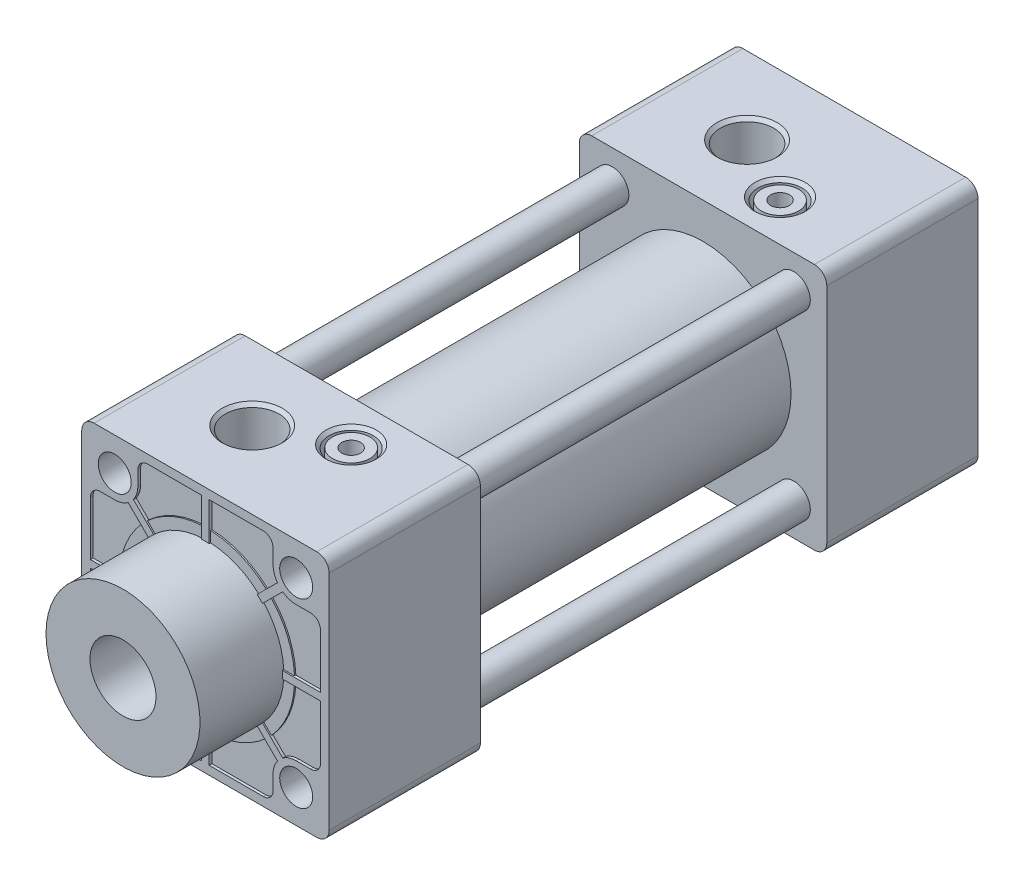
SolidWorks part; units mm, degrees
ref_plane "前视基准面" through (0, 0, 0) normal (0, 0, 1) x (1, 0, 0)
ref_plane "上视基准面" through (0, 0, 0) normal (0, 1, 0) x (1, 0, 0)
ref_plane "右视基准面" through (0, 0, 0) normal (1, 0, 0) x (0, 0, -1)
sketch "草图1" plane through (0, 0, 0) normal (1, 0, 0) x (0, 0, -1)
  line L0 (-59, 0) -> (59, 0) construction
  line L1 (0, 0) -> (0, 22.5) construction
  line L3 (-59, 0) -> (-59, 14) construction
  line L4 (-59, 14) -> (-74, 14) construction
  line L7 (-74, 14) -> (-74, 0) construction
  line L8 (25, 22.5) -> (118, 22.5) construction
  line L9 (-106, 0) -> (-106, 5) construction
  line L10 (-84, 0) -> (-106, 0) construction
  circle A0 centre (45, 5.5) radius 4.8645
  circle A1 centre (39, -6.5) radius 4
  point P2 (-106, 0)
  point P6 (-31.5, 0)
  point P10 (45, 5.5)
  point P11 (39, -6.5)
  point P15 (-49.5, 0)
  point P20 (31.5, 0)
  point P21 (-74, 6)
  point P22 (25, 22.5)
  point P25 (-97.2, 0)
  point P28 (-91.2, 0)
  point P29 (0, 16)
  dimension "O" = 9.729
  dimension "D3" = 8
  dimension "C" = 118
  dimension "S" = 45
  dimension "G" = 27.5
  dimension "N" = 14
  dimension "P" = 5.5
  dimension "Q" = 6
  dimension "R" = 6.5
  dimension "D" = 28
  dimension "F" = 15
  dimension "D4" = 8.8
  dimension "V" = 12
  dimension "行程" = 25
  dimension "C用" = 93
  dimension "B" = 47
  dimension "H" = 22
  dimension "J" = 6
  dimension "K" = 10
  dimension "M" = 9.5
  dimension "DD" = 32
sketch "草图2" plane through (0, 0, 0) normal (0, 0, 1) x (1, 0, 0)
  line L0 (0, 0) -> (0, 22.5) construction
  line L1 (-20.25, -22.5) -> (20.25, -22.5)
  line L2 (-22.5, -20.25) -> (-22.5, 20.25)
  line L3 (-20.25, 22.5) -> (20.25, 22.5)
  line L4 (22.5, -20.25) -> (22.5, 20.25)
  line L5 (-22.5, -22.5) -> (22.5, 22.5) construction
  line L6 (-22.5, 22.5) -> (22.5, -22.5) construction
  line L8 (0, 9.815) -> (-8.5, 4.9075)
  line L9 (-8.5, 4.9075) -> (-8.5, -4.9075)
  line L10 (-8.5, -4.9075) -> (0, -9.815)
  line L11 (0, -9.815) -> (8.5, -4.9075)
  line L12 (8.5, -4.9075) -> (8.5, 4.9075)
  line L13 (8.5, 4.9075) -> (0, 9.815)
  line L14 (0, 7.0711) -> (-7.0711, 0)
  line L15 (-7.0711, 0) -> (0, -7.0711)
  line L16 (0, -7.0711) -> (7.0711, 0)
  line L17 (7.0711, 0) -> (0, 7.0711)
  arc A0 (20.25, 22.5) -> (22.5, 20.25) centre (20.25, 20.25) cw
  arc A1 (20.25, -22.5) -> (22.5, -20.25) centre (20.25, -20.25) ccw
  arc A2 (-20.25, -22.5) -> (-22.5, -20.25) centre (-20.25, -20.25) cw
  arc A3 (-22.5, 20.25) -> (-20.25, 22.5) centre (-20.25, 20.25) cw
  circle A4 centre (-16.5, 16.5) radius 3
  circle A5 centre (0, 0) radius 8.5 construction
  circle A6 centre (0, 0) radius 5 construction
  point P0 (0, 0)
  point P19 (-16.5, 16.5)
  dimension "D1" = 2.25
  dimension "L" = 6
  dimension "I" = 17
  dimension "W" = 10
  dimension "T" = 33
sketch "行程" plane through (0, 0, 0) normal (1, 0, 0) x (0, 0, -1)
  line L0 (31.5, 0) -> (6.5, 0)
  line L1 (-59, 0) -> (59, 0) construction
  line L2 (31.5, 0) -> (31.5, 1)
  line L3 (6.5, 0) -> (6.5, 1)
  dimension "D1" = 25
  dimension "D2" = 1
sketch "草图3" plane through (0, 0, 0) normal (0, 0, 1) x (1, 0, 0)
  line L0 (-22.5, -20.25) -> (-22.5, 20.25) construction
  line L1 (-20.25, -22.5) -> (20.25, -22.5) construction
  line L2 (22.5, -20.25) -> (22.5, 20.25) construction
  line L3 (-20.25, 22.5) -> (20.25, 22.5) construction
  line L4 (-22.5, -20.25) -> (-22.5, 20.25)
  line L5 (-20.25, -22.5) -> (20.25, -22.5)
  line L6 (22.5, -20.25) -> (22.5, 20.25)
  line L7 (-20.25, 22.5) -> (20.25, 22.5)
  arc A1 (-22.5, -20.25) -> (-20.25, -22.5) centre (-20.25, -20.25) ccw construction
  arc A2 (20.25, -22.5) -> (22.5, -20.25) centre (20.25, -20.25) ccw construction
  arc A3 (22.5, 20.25) -> (20.25, 22.5) centre (20.25, 20.25) ccw construction
  arc A4 (-20.25, 22.5) -> (-22.5, 20.25) centre (-20.25, 20.25) ccw construction
  arc A6 (-22.5, -20.25) -> (-20.25, -22.5) centre (-20.25, -20.25) ccw
  arc A7 (20.25, -22.5) -> (22.5, -20.25) centre (20.25, -20.25) ccw
  arc A8 (22.5, 20.25) -> (20.25, 22.5) centre (20.25, 20.25) ccw
  arc A9 (-20.25, 22.5) -> (-22.5, 20.25) centre (-20.25, 20.25) ccw
extrude "凸台-拉伸1" add sketch "草图3" against normal up to vertex (59 mm away) from vertex at 59 starting at point (0, 0, 59)
sketch "草图4" plane through (0, 0, 0) normal (0, 0, 1) x (1, 0, 0)
  line L0 (-22.5, -20.25) -> (-22.5, 20.25) construction
  line L1 (-20.25, 22.5) -> (20.25, 22.5) construction
  line L2 (22.5, -20.25) -> (22.5, 20.25) construction
  line L3 (-20.25, -22.5) -> (20.25, -22.5) construction
  line L4 (-22.5, -20.25) -> (-22.5, 20.25)
  line L5 (-20.25, 22.5) -> (20.25, 22.5)
  line L6 (22.5, -20.25) -> (22.5, 20.25)
  line L7 (-20.25, -22.5) -> (20.25, -22.5)
  circle A0 centre (0, 0) radius 16
  arc A1 (-20.25, 22.5) -> (-22.5, 20.25) centre (-20.25, 20.25) ccw construction
  arc A2 (22.5, 20.25) -> (20.25, 22.5) centre (20.25, 20.25) ccw construction
  arc A3 (20.25, -22.5) -> (22.5, -20.25) centre (20.25, -20.25) ccw construction
  arc A4 (-22.5, -20.25) -> (-20.25, -22.5) centre (-20.25, -20.25) ccw construction
  arc A5 (-20.25, 22.5) -> (-22.5, 20.25) centre (-20.25, 20.25) ccw
  arc A6 (22.5, 20.25) -> (20.25, 22.5) centre (20.25, 20.25) ccw
  arc A7 (20.25, -22.5) -> (22.5, -20.25) centre (20.25, -20.25) ccw
  arc A8 (-22.5, -20.25) -> (-20.25, -22.5) centre (-20.25, -20.25) ccw
  dimension "D1" = 32
extrude "切除-拉伸1" cut sketch "草图4" along normal up to vertex (31.5 mm away) from vertex at -31.5 starting at point (0, 0, -31.5)
sketch "草图17" plane through (0, 0, 59) normal (0, 0, 1) x (1, 0, 0)
  line L0 (-10.5, -20.925) -> (10.5, -20.925)
  line L1 (20.925, -10.5) -> (20.925, 10.5)
  line L2 (10.5, 20.925) -> (-10.5, 20.925)
  line L3 (-20.925, 10.5) -> (-20.925, -10.5)
  line L4 (-20.25, -22.5) -> (20.25, -22.5)
  line L5 (22.5, -20.25) -> (22.5, 20.25)
  line L6 (20.25, 22.5) -> (-20.25, 22.5)
  line L7 (-22.5, 20.25) -> (-22.5, -20.25)
  line L8 (-20.25, -22.5) -> (20.25, -22.5) construction
  line L9 (22.5, -20.25) -> (22.5, 20.25) construction
  line L10 (20.25, 22.5) -> (-20.25, 22.5) construction
  line L11 (-22.5, 20.25) -> (-22.5, -20.25) construction
  line L12 (-12.3, 16.5) -> (-12.3, 19.125)
  line L13 (-16.5, 12.3) -> (-19.125, 12.3)
  line L14 (16.5, 12.3) -> (19.125, 12.3)
  line L15 (-20.925, 20.25) -> (-20.925, -20.25) construction
  line L16 (20.25, 20.925) -> (-20.25, 20.925) construction
  line L17 (12.3, 16.5) -> (12.3, 19.125)
  line L18 (12.3, -16.5) -> (12.3, -19.125)
  line L19 (16.5, -12.3) -> (19.125, -12.3)
  line L20 (-16.5, -12.3) -> (-19.125, -12.3)
  line L21 (-12.3, -16.5) -> (-12.3, -19.125)
  line L22 (-22.5, -22.5) -> (22.5, 22.5) construction
  line L24 (20.925, -20.25) -> (20.925, 20.25) construction
  line L25 (-20.25, -20.925) -> (20.25, -20.925) construction
  arc A0 (-19.125, 12.3) -> (-20.925, 10.5) centre (-19.125, 10.5) ccw
  arc A1 (-19.125, -12.3) -> (-20.925, -10.5) centre (-19.125, -10.5) cw
  arc A2 (12.3, 16.5) -> (16.5, 12.3) centre (16.5, 16.5) ccw
  arc A3 (-12.3, -19.125) -> (-10.5, -20.925) centre (-10.5, -19.125) ccw
  arc A4 (-22.5, -20.25) -> (-20.25, -22.5) centre (-20.25, -20.25) ccw
  arc A5 (20.25, -22.5) -> (22.5, -20.25) centre (20.25, -20.25) ccw
  arc A6 (22.5, 20.25) -> (20.25, 22.5) centre (20.25, 20.25) ccw
  arc A7 (-20.25, 22.5) -> (-22.5, 20.25) centre (-20.25, 20.25) ccw
  arc A8 (-22.5, -20.25) -> (-20.25, -22.5) centre (-20.25, -20.25) ccw construction
  arc A9 (20.25, -22.5) -> (22.5, -20.25) centre (20.25, -20.25) ccw construction
  arc A10 (22.5, 20.25) -> (20.25, 22.5) centre (20.25, 20.25) ccw construction
  arc A11 (-20.25, 22.5) -> (-22.5, 20.25) centre (-20.25, 20.25) ccw construction
  arc A12 (-16.5, 12.3) -> (-12.3, 16.5) centre (-16.5, 16.5) ccw
  arc A13 (-20.25, 20.925) -> (-20.925, 20.25) centre (-20.25, 20.25) ccw construction
  arc A14 (16.5, -12.3) -> (12.3, -16.5) centre (16.5, -16.5) ccw
  arc A15 (-12.3, -16.5) -> (-16.5, -12.3) centre (-16.5, -16.5) ccw
  arc A16 (20.925, 20.25) -> (20.25, 20.925) centre (20.25, 20.25) ccw construction
  arc A17 (20.25, -20.925) -> (20.925, -20.25) centre (20.25, -20.25) ccw construction
  arc A18 (-20.925, -20.25) -> (-20.25, -20.925) centre (-20.25, -20.25) ccw construction
  arc A19 (12.3, -19.125) -> (10.5, -20.925) centre (10.5, -19.125) cw
  arc A20 (19.125, -12.3) -> (20.925, -10.5) centre (19.125, -10.5) ccw
  arc A21 (19.125, 12.3) -> (20.925, 10.5) centre (19.125, 10.5) cw
  arc A22 (12.3, 19.125) -> (10.5, 20.925) centre (10.5, 19.125) ccw
  arc A23 (-12.3, 19.125) -> (-10.5, 20.925) centre (-10.5, 19.125) cw
  dimension "D3" = 8.4
  dimension "D5" = 1.8
  dimension "D4" = 4
  dimension "D1" = 0
  dimension "D2" = 1.575
extrude "切除-拉伸10" cut sketch "草图17" against normal blind 0.5
sketch "草图5" plane through (0, 0, 0) normal (1, 0, 0) x (0, 0, -1)
  line L0 (-74, 14) -> (-74, 0) construction
  line L3 (-59, 14) -> (-74, 14) construction
  line L4 (-74, 14) -> (-74, 0)
  line L7 (-58.5, 14) -> (-74, 14)
  line L8 (-58.5, 14) -> (-58.5, 0)
  line L9 (-58.5, 0) -> (-74, 0)
  line L10 (-58.5, 10.5) -> (-58.5, -10.5) construction
sketch "草图18" plane through (0, 0, 58.5) normal (0, 0, 1) x (1, 0, 0)
  line L0 (-0.675, 22.5) -> (-0.675, 0)
  line L2 (0, 22.5) -> (0, 0) construction
  line L3 (0.675, 22.5) -> (0.675, 0)
  line L4 (-0.675, 22.5) -> (0.675, 22.5)
  line L5 (-0.675, 0) -> (0.675, 0)
  line L6 (20.25, 22.5) -> (-20.25, 22.5) construction
  dimension "D1" = 1.35
extrude "凸台-拉伸7" add sketch "草图18" along normal up to surface (0.5 mm away) up to face at (0, 0, 59)
sketch "草图20" plane through (0, 0, 58.5) normal (0, 0, 1) x (1, 0, 0)
  circle A0 centre (0, 0) radius 15.96
  dimension "D1" = 31.92
extrude "凸台-拉伸8" add sketch "草图20" along normal blind 0.25
pattern_circular "阵列(圆周)3" count 8 over 360 about axis through (0, 0, 0) along (0, 0, 1) of "凸台-拉伸7"
mirror "镜向3" about plane through (0, 0, 0) normal (0, 0, 1) of "切除-拉伸10"
sketch "草图21" plane through (0, 0, -58.5) normal (0, 0, -1) x (-1, 0, 0)
  line L0 (0.675, 22.5) -> (0.675, 0) construction
  line L1 (0.675, 0) -> (-0.675, 0) construction
  line L2 (-0.675, 22.5) -> (-0.675, 0) construction
  line L3 (0.675, 22.5) -> (-0.675, 22.5) construction
  line L4 (0.675, 22.5) -> (0.675, 0)
  line L5 (0.675, 0) -> (-0.675, 0)
  line L6 (-0.675, 22.5) -> (-0.675, 0)
  line L7 (0.675, 22.5) -> (-0.675, 22.5)
extrude "凸台-拉伸9" add sketch "草图21" along normal up to surface (0.5 mm away) up to face at (0, 0, -59)
sketch "草图22" plane through (0, 0, -58.5) normal (0, 0, -1) x (-1, 0, 0)
  circle A0 centre (0, 0) radius 15.96 construction
  circle A1 centre (0, 0) radius 15.96
extrude "凸台-拉伸10" add sketch "草图22" along normal up to surface (0.5 mm away)
pattern_circular "阵列(圆周)4" count 8 over 360 about axis through (0, 0, 0) along (0, 0, 1) of "凸台-拉伸9"
revolve "旋转2" add sketch "草图5" angle 360 mid plane about L9
sketch "草图6" plane through (0, 0, -31.5) normal (0, 0, 1) x (1, 0, 0)
  line L0 (0, 0) -> (0, 22.5) construction
  line L1 (20.25, 22.5) -> (-20.25, 22.5) construction
  line L2 (0, 0) -> (-22.5, 0) construction
  line L3 (-22.5, 20.25) -> (-22.5, -20.25) construction
  circle A1 centre (-16.5, 16.5) radius 3
  dimension "D2" = 6
extrude "凸台-拉伸2" add sketch "草图6" along normal up to surface (63 mm away) up to face at (0, 0, 31.5)
pattern_circular "阵列(圆周)1" count 4 over 360 about axis through (0, 0, 0) along (0, 0, 1) of "凸台-拉伸2"
sketch "草图7" plane through (22.5, 0, 0) normal (1, 0, 0) x (0, 0, -1)
  circle A0 centre (45, 5.5) radius 4.8645 construction
  circle A1 centre (39, -6.5) radius 4 construction
  circle A2 centre (45, 5.5) radius 4.8645
  circle A3 centre (39, -6.5) radius 4
extrude "切除-拉伸3" cut sketch "草图7" against normal blind 9
cosmetic thread "装饰螺纹线5" parameters "D2"=9.829
mirror "镜向1" about plane through (0, 0, 0) normal (0, 0, 1) of "切除-拉伸3"
sketch "草图15" plane through (13.5, 0, 0) normal (1, 0, 0) x (0, 0, -1)
  circle A0 centre (39, -6.5) radius 3.4
  dimension "D1" = 6.8
extrude "凸台-拉伸4" add sketch "草图15" along normal offset from surface (8.5 mm away) 0.5 up to face at (22.5, -6.5, -43)
sketch "草图16" plane through (22, 0, 0) normal (1, 0, 0) x (0, 0, -1)
  circle A0 centre (39, -6.5) radius 1.7
  dimension "D1" = 3.4
extrude "切除-拉伸9" cut sketch "草图16" against normal offset from surface (8 mm away) 0.5 up to face at (13.5, -6.5, -43)
mirror "镜向2" about plane through (0, 0, 0) normal (0, 0, 1) of "凸台-拉伸4", "切除-拉伸9"
sketch "草图23" plane through (0, 0, 59) normal (0, 0, 1) x (1, 0, 0)
  circle A0 centre (-16.5, 16.5) radius 3 construction
  circle A1 centre (-16.5, 16.5) radius 3
extrude "切除-拉伸11" cut sketch "草图23" against normal blind 9.5
cosmetic thread "装饰螺纹线6" parameters "D2"=6.1
pattern_circular "阵列(圆周)5" count 4 over 360 about axis through (0, 0, 0) along (0, 0, 1) of "切除-拉伸11"
mirror "镜向5" about plane through (0, 0, 0) normal (0, 0, 1) of "阵列(圆周)5", "切除-拉伸11"
sketch "草图24" plane through (0, 0, 74) normal (0, 0, 1) x (1, 0, 0)
  circle A0 centre (0, 0) radius 6
extrude "切除-拉伸12" cut sketch "草图24" against normal up to vertex (105.5 mm away) up to point (0, 0, -31.5)
chamfer "倒角2" distance 0.5973 angle 45 2 edges at (22.5, 5.5, 49.8645) (22.5, 5.5, -49.8645)
chamfer "倒角3" distance 0.58 angle 45 2 edges at (22.5, -6.5, 43) (22.5, -6.5, -43)
move or copy body "实体-移动/复制1" bodies to move or copy 133 copy no rotation origin (0, 0, 0) rotation axis (0, 0, 1) rotation angle 90
